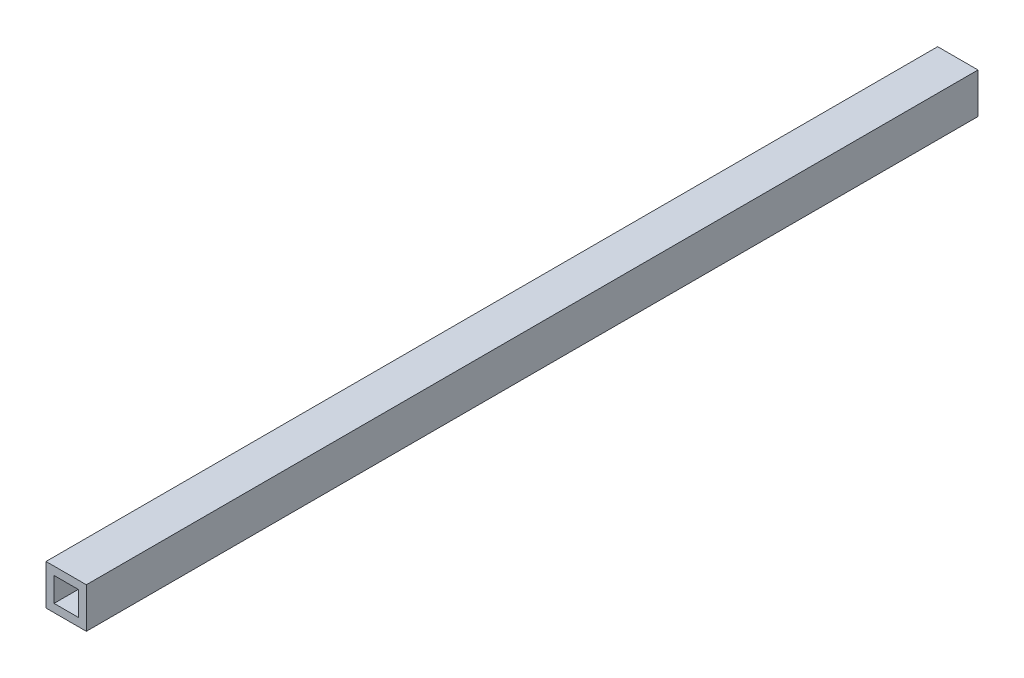
SolidWorks part; units mm, degrees
ref_plane "Front Plane" through (0, 0, 0) normal (0, 0, 1) x (1, 0, 0)
ref_plane "Top Plane" through (0, 0, 0) normal (0, 1, 0) x (1, 0, 0)
ref_plane "Right Plane" through (0, 0, 0) normal (1, 0, 0) x (0, 0, -1)
sketch "Sketch1" plane through (0, 0, 0) normal (0, 0, 1) x (1, 0, 0)
  line L0 (-3, 3) -> (3, 3)
  line L1 (-5, -5) -> (5, -5)
  line L2 (-5, -5) -> (-5, 5)
  line L3 (-5, 5) -> (5, 5)
  line L4 (5, -5) -> (5, 5)
  line L5 (-5, -5) -> (5, 5) construction
  line L6 (-5, 5) -> (5, -5) construction
  line L7 (3, -3) -> (3, 3)
  line L8 (-3, -3) -> (3, -3)
  line L9 (-3, -3) -> (-3, 3)
  point P0 (0, 0)
  dimension "D1" = 10
  dimension "D2" = 2
extrude "Boss-Extrude1" add sketch "Sketch1" along normal blind 221
